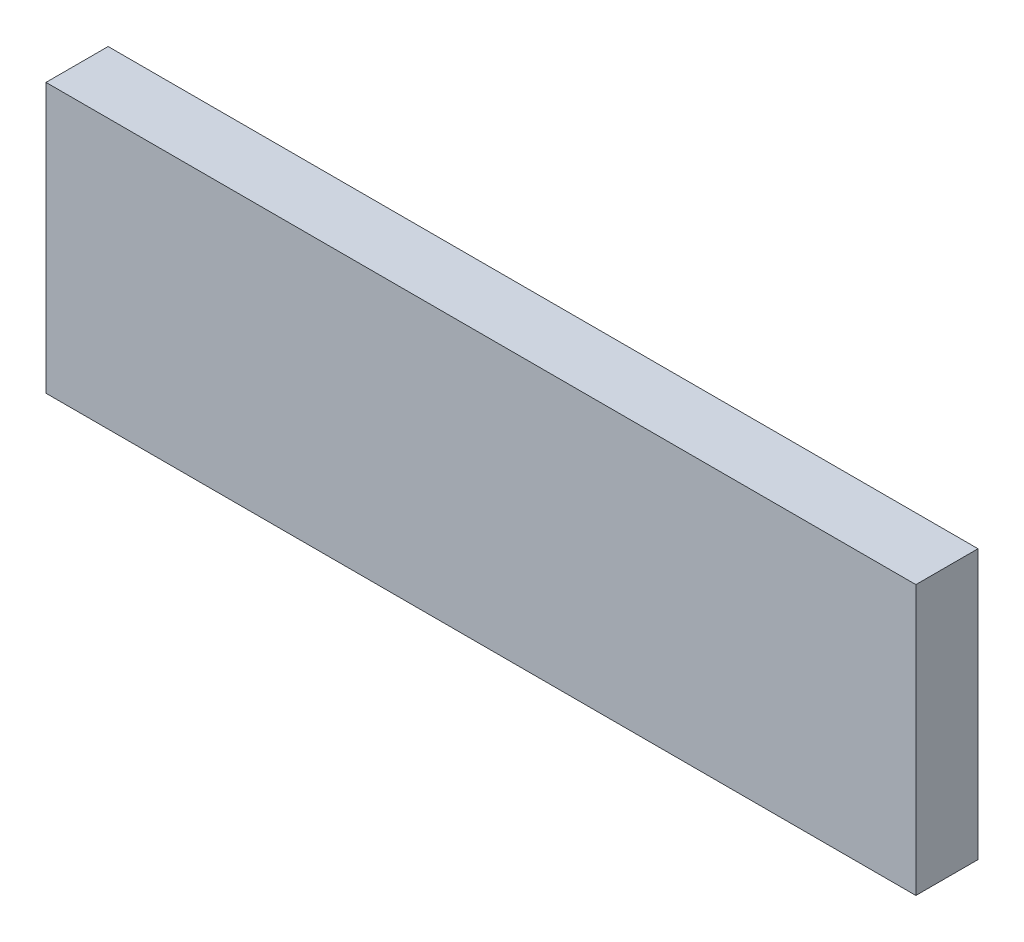
SolidWorks part; units mm, degrees
ref_plane "Front Plane" through (0, 0, 0) normal (0, 0, 1) x (1, 0, 0)
ref_plane "Top Plane" through (0, 0, 0) normal (0, 1, 0) x (1, 0, 0)
ref_plane "Right Plane" through (0, 0, 0) normal (1, 0, 0) x (0, 0, -1)
sketch "Sketch1" plane through (0, 0, 0) normal (0, 0, 1) x (1, 0, 0)
  line L1 (0, 0) -> (42, 0)
  line L2 (0, 0) -> (0, 13)
  line L3 (0, 13) -> (42, 13)
  line L4 (42, 0) -> (42, 13)
  dimension "D1" = 42
  dimension "D2" = 13
extrude "Boss-Extrude1" add sketch "Sketch1" along normal blind 3
